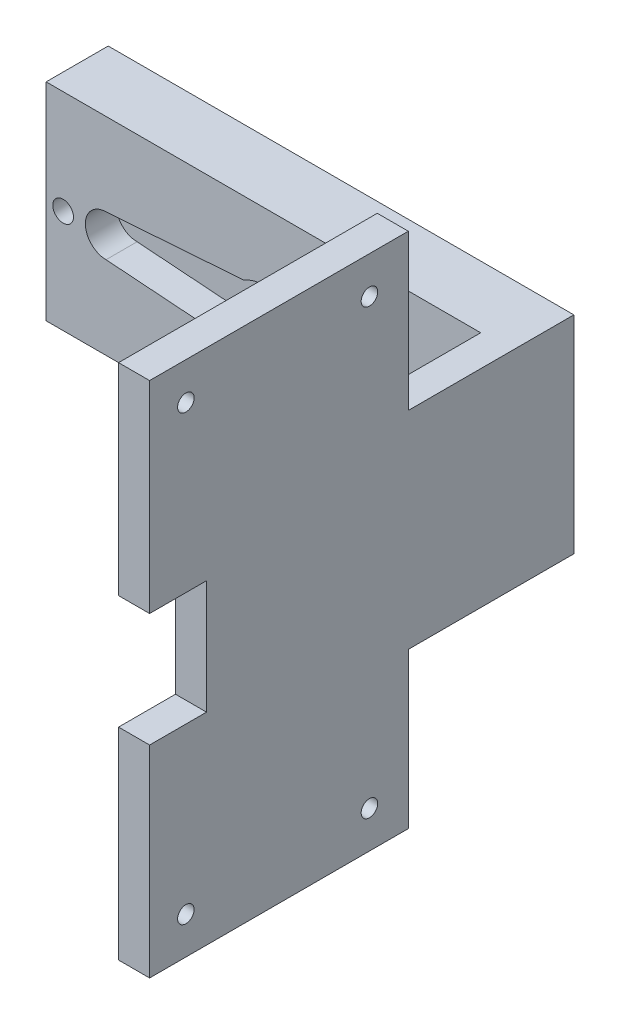
SolidWorks part; units mm, degrees
ref_plane "Alzado" through (0, 0, 0) normal (0, 0, 1) x (1, 0, 0)
ref_plane "Planta" through (0, 0, 0) normal (0, 1, 0) x (1, 0, 0)
ref_plane "Vista lateral" through (0, 0, 0) normal (1, 0, 0) x (0, 0, -1)
sketch "Croquis1" plane through (0, 0, 0) normal (0, 0, 1) x (1, 0, 0)
  line L1 (-22.5, -10) -> (22.5, -10)
  line L2 (-22.5, -10) -> (-22.5, 10)
  line L3 (-22.5, 10) -> (22.5, 10)
  line L4 (22.5, -10) -> (22.5, 10)
  line L5 (-22.5, -10) -> (22.5, 10) construction
  line L6 (-22.5, 10) -> (22.5, -10) construction
  point P0 (0, 0)
  dimension "D1" = 45
  dimension "D2" = 20
extrude "Saliente-Extruir1" add sketch "Croquis1" along normal blind 6
sketch "Croquis2" plane through (0, 0, 6) normal (0, 0, 1) x (1, 0, 0)
  line L0 (-22.5, -10) -> (22.5, -10) construction
  line L1 (22.5, 10) -> (19.5, 10)
  line L2 (22.5, 10) -> (22.5, -10)
  line L3 (22.5, -10) -> (19.5, -10)
  line L4 (19.5, 10) -> (19.5, -10)
  dimension "D1" = 3
extrude "Saliente-Extruir2" add sketch "Croquis2" along normal blind 10
sketch "Croquis3" plane through (0, 0, 16) normal (0, 0, 1) x (1, 0, 0)
  line L0 (19.5, 0) -> (19.5, 25)
  line L1 (19.5, 10) -> (19.5, -10) construction
  line L2 (19.5, 0) -> (19.5, -25)
  line L3 (19.5, -25) -> (22.5, -25)
  line L4 (22.5, -25) -> (22.5, 25)
  line L5 (22.5, 25) -> (19.5, 25)
  dimension "D1" = 25
  dimension "D2" = 25
extrude "Saliente-Extruir3" add sketch "Croquis3" along normal blind 25
sketch "Croquis4" plane through (22.5, 0, 0) normal (1, 0, 0) x (0, 0, -1)
  line L0 (-41, -25) -> (-41, 25) construction
  line L1 (-46.5, -5.5) -> (-35.5, -5.5)
  line L2 (-46.5, -5.5) -> (-46.5, 5.5)
  line L3 (-46.5, 5.5) -> (-35.5, 5.5)
  line L4 (-35.5, -5.5) -> (-35.5, 5.5)
  line L5 (-46.5, -5.5) -> (-35.5, 5.5) construction
  line L6 (-46.5, 5.5) -> (-35.5, -5.5) construction
  circle A0 centre (-19.7563, -21.41) radius 0.8
  circle A1 centre (-37.4963, -21.41) radius 0.8
  circle A2 centre (-19.7563, 21.41) radius 0.8
  circle A3 centre (-37.4963, 21.41) radius 0.8
  point P8 (-41, 0)
  dimension "D1" = 1.6
  dimension "D2" = 11
  dimension "D3" = 11
extrude "Cortar-Extruir1" cut sketch "Croquis4" against normal through all
sketch "Croquis5" plane through (0, 0, 6) normal (0, 0, 1) x (1, 0, 0)
  line L0 (-22.5, -10) -> (-22.5, 10) construction
  line L1 (-22.5, 10) -> (-22.5, -10) construction
  line L2 (19.5, 10) -> (-22.5, 10) construction
  line L3 (-22.5, 0) -> (19.5, 0) construction
  line L4 (19.5, -5.5) -> (19.5, 5.5) construction
  line L5 (-20.8579, 0) -> (-20.8579, -10) construction
  line L6 (-22.5, -10) -> (19.5, -10) construction
  line L7 (-20.8579, 0) -> (7.5799, 0) construction
  circle A0 centre (-20.8579, 0) radius 0.9989
  circle A2 centre (7.6421, 0) radius 1
  dimension "D2" = 1.9978
extrude "Cortar-Extruir2" cut sketch "Croquis5" against normal through all
sketch "Croquis6" plane through (0, 0, 6) normal (0, 0, 1) x (1, 0, 0)
  line L0 (-16.7064, 2.0114) -> (-3.3742, 2.9609)
  line L1 (-3.3742, 2.9609) -> (0.3629, 2.9581)
  line L2 (0.3629, 2.9581) -> (13.5884, 1.9962)
  line L3 (-16.7094, -1.9886) -> (-3.3787, -2.9581)
  line L4 (-3.3787, -2.9581) -> (0.3585, -2.9609)
  line L5 (0.3585, -2.9609) -> (13.5854, -2.0189)
  arc A0 (13.5854, -2.0189) -> (13.5884, 1.9962) centre (13.6921, -0.0114) ccw
  arc A1 (-16.7064, 2.0114) -> (-16.7094, -1.9886) centre (-16.7079, 0.0114) ccw
extrude "Cortar-Extruir3" cut sketch "Croquis6" against normal blind 3
sketch "Croquis7" plane through (0, 0, 6) normal (0, 0, 1) x (1, 0, 0)
  circle A0 centre (-1.5079, 0) radius 3.5
  dimension "D1" = 7
extrude "Cortar-Extruir4" cut sketch "Croquis7" against normal through all
